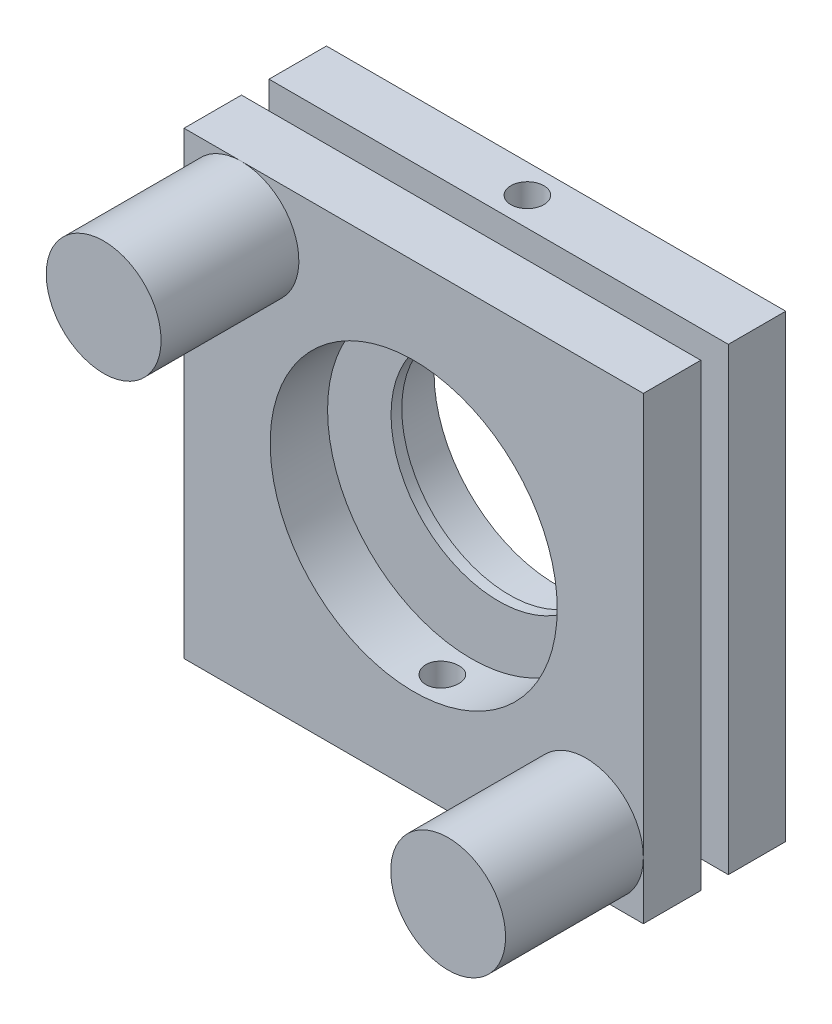
SolidWorks part; units mm, degrees
ref_plane "Front Plane" through (0, 0, 0) normal (0, 0, 1) x (1, 0, 0)
ref_plane "Top Plane" through (0, 0, 0) normal (0, 1, 0) x (1, 0, 0)
ref_plane "Right Plane" through (0, 0, 0) normal (1, 0, 0) x (0, 0, -1)
sketch "Sketch1" plane through (0, 0, 0) normal (0, 0, 1) x (1, 0, 0)
  line L1 (-25.4, -25.4) -> (25.4, -25.4)
  line L2 (-25.4, -25.4) -> (-25.4, 25.4)
  line L3 (-25.4, 25.4) -> (25.4, 25.4)
  line L4 (25.4, -25.4) -> (25.4, 25.4)
  line L5 (-25.4, -25.4) -> (25.4, 25.4) construction
  line L6 (-25.4, 25.4) -> (25.4, -25.4) construction
  circle A0 centre (0, 0) radius 13.4938
  point P0 (0, 0)
  dimension "D3" = 26.9875
  dimension "D1" = 50.8
  dimension "D2" = 50.8
extrude "Boss-Extrude1" add sketch "Sketch1" along normal blind 6.35
pattern_linear "LPattern2" count 2 spacing 9.398 along (0, 0, 1) of bodies 101
sketch "Sketch2" plane through (0, 0, 6.35) normal (0, 0, 1) x (1, 0, 0)
  line L4 (25.4, -25.4) -> (25.4, 25.4)
  line L5 (25.4, 25.4) -> (-25.4, 25.4)
  line L6 (-25.4, 25.4) -> (-25.4, -25.4)
  line L7 (-25.4, -25.4) -> (25.4, -25.4)
  line L8 (25.4, -25.4) -> (25.4, 25.4)
  line L9 (25.4, 25.4) -> (-25.4, 25.4)
  line L10 (-25.4, 25.4) -> (-25.4, -25.4)
  line L11 (-25.4, -25.4) -> (25.4, -25.4)
  circle A0 centre (0, 0) radius 11.9062
  dimension "D1" = 23.8125
  dimension "D2" = 0
extrude "Boss-Extrude2" add sketch "Sketch2" against normal blind 1.1906
sketch "Sketch3" plane through (0, 25.4, 0) normal (0, 1, 0) x (1, 0, 0)
  circle A0 centre (0, -3.175) radius 1.825
  dimension "D1" = 3.65
extrude "Cut-Extrude1" cut sketch "Sketch3" against normal blind 19.05
sketch "Sketch5" plane through (0, 0, 15.748) normal (0, 0, 1) x (1, 0, 0)
  circle A0 centre (0, 0) radius 15.875
  dimension "D1" = 31.75
extrude "Cut-Extrude2" cut sketch "Sketch5" against normal up to surface (6.35 mm away) up to face at (0, 0, 9.398)
sketch "Sketch6" plane through (0, -25.4, 0) normal (0, -1, 0) x (1, 0, 0)
  line L0 (-25.4, 15.748) -> (-25.4, 9.398) construction
  circle A0 centre (0, 12.573) radius 1.825
  point P6 (-25.4, 12.573)
  dimension "D1" = 3.65
extrude "Cut-Extrude3" cut sketch "Sketch6" against normal up to surface (9.525 mm away)
sketch "Sketch7" plane through (0, 0, 15.748) normal (0, 0, 1) x (1, 0, 0)
  line L4 (25.4, -25.4) -> (25.4, 25.4)
  line L5 (25.4, 25.4) -> (-25.4, 25.4)
  line L6 (-25.4, 25.4) -> (-25.4, -25.4)
  line L7 (-25.4, -25.4) -> (25.4, -25.4)
  line L8 (25.4, -25.4) -> (25.4, 25.4) construction
  line L9 (25.4, 25.4) -> (-25.4, 25.4) construction
  line L10 (-25.4, 25.4) -> (-25.4, -25.4) construction
  line L11 (-25.4, -25.4) -> (25.4, -25.4) construction
  circle A0 centre (19.05, -19.05) radius 6.35
  circle A1 centre (-19.05, 19.05) radius 6.35
  dimension "D2" = 12.7
  dimension "D3" = 12.7
  dimension "D1" = 0
extrude "Boss-Extrude3" add sketch "Sketch7" along normal blind 15.24
sketch "Sketch8" plane through (0, 0, 9.398) normal (0, 0, -1) x (-1, 0, 0)
  circle A0 centre (-19.05, -19.05) radius 3.175
  circle A1 centre (19.05, 19.05) radius 3.175
  circle A2 centre (-19.05, -19.05) radius 6.35 construction
  circle A3 centre (19.05, 19.05) radius 6.35 construction
  circle A4 centre (-19.05, -19.05) radius 6.35
  circle A5 centre (19.05, 19.05) radius 6.35
  dimension "D1" = 6.35
  dimension "D2" = 6.35
extrude "Boss-Extrude4" add sketch "Sketch8" along normal up to surface (9.398 mm away) contours A0 | A1 up to face at (0, 0, 0)
